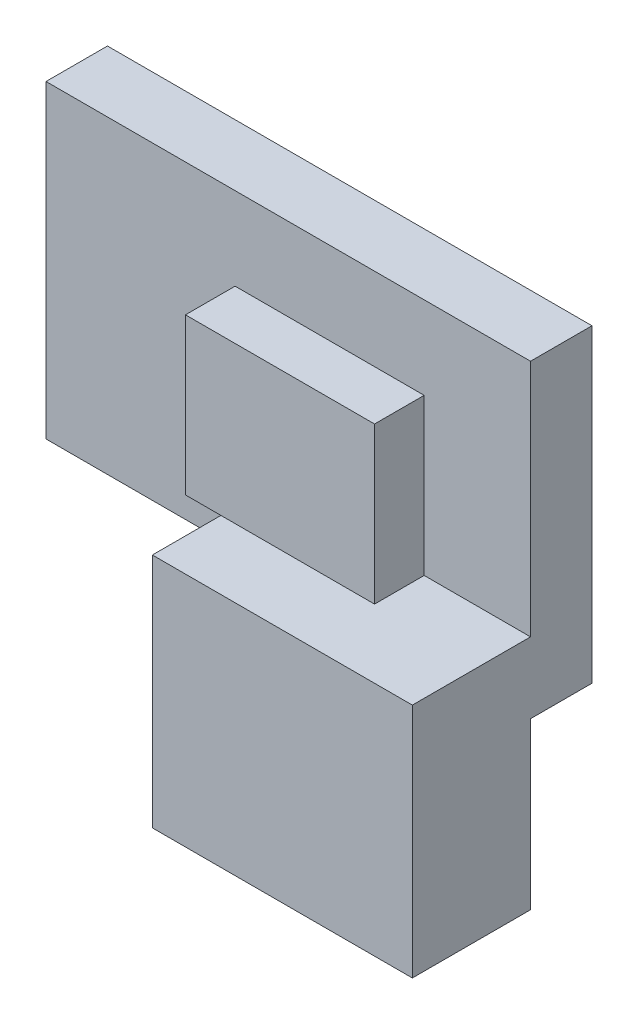
SolidWorks part; units mm, degrees
ref_plane "Plano frontal" through (0, 0, 0) normal (0, 0, 1) x (1, 0, 0)
ref_plane "Plano superior" through (0, 0, 0) normal (0, 1, 0) x (1, 0, 0)
ref_plane "Plano direito" through (0, 0, 0) normal (1, 0, 0) x (0, 0, -1)
sketch "PlacaEsboco" plane through (0, 0, 0) normal (0, 0, 1) x (1, 0, 0)
  line L1 (-10.25, -6.55) -> (10.25, -6.55)
  line L2 (-10.25, -6.55) -> (-10.25, 6.55)
  line L3 (-10.25, 6.55) -> (10.25, 6.55)
  line L4 (10.25, -6.55) -> (10.25, 6.55)
  line L5 (-10.25, -6.55) -> (10.25, 6.55) construction
  line L6 (-10.25, 6.55) -> (10.25, -6.55) construction
  point P0 (0, 0)
  dimension "D1" = 13.1
  dimension "D2" = 20.5
extrude "Placa" add sketch "PlacaEsboco" along normal mid plane 2.6
sketch "ConectorEsboco" plane through (0, 0, 1.3) normal (0, 0, 1) x (1, 0, 0)
  line L0 (10.25, -6.55) -> (10.25, 6.55) construction
  line L1 (10.25, -3.55) -> (-0.75, -3.55)
  line L2 (10.25, -3.55) -> (10.25, -13.55)
  line L3 (10.25, -13.55) -> (-0.75, -13.55)
  line L4 (-0.75, -3.55) -> (-0.75, -13.55)
  dimension "D1" = 11
  dimension "D2" = 10
  dimension "D3" = 3
extrude "Conector" add sketch "ConectorEsboco" along normal blind 5
sketch "ResistoresEsboco" plane through (0, 0, 1.3) normal (0, 0, 1) x (1, 0, 0)
  line L0 (10.25, -3.55) -> (-0.75, -3.55) construction
  line L1 (5.75, 3.05) -> (-2.25, 3.05)
  line L2 (5.75, 3.05) -> (5.75, -3.55)
  line L3 (5.75, -3.55) -> (-2.25, -3.55)
  line L4 (-2.25, 3.05) -> (-2.25, -3.55)
  dimension "D1" = 12.5
  dimension "D2" = 4.5
  dimension "D3" = 3.5
extrude "Resistores" add sketch "ResistoresEsboco" along normal blind 2.1
sketch "PosLedLDR" plane through (0, 0, 1.3) normal (0, 0, 1) x (1, 0, 0)
  line L0 (10.25, 6.55) -> (-10.25, 6.55) construction
  line L1 (-10.25, 6.55) -> (-10.25, -6.55) construction
  circle A0 centre (-6.25, 4.55) radius 0.25
  circle A1 centre (-6.25, 3.05) radius 0.25
  circle A2 centre (-6.25, -3.45) radius 0.25
  circle A3 centre (-6.25, -4.95) radius 0.25
  point P0 (-6.25, 4.55)
  point P1 (-6.25, 3.05)
  point P2 (-6.25, -3.45)
  point P3 (-6.25, -4.95)
  dimension "D6" = 0.5
  dimension "D7" = 0.5
  dimension "D8" = 0.5
  dimension "D9" = 0.5
  dimension "D1" = 2
  dimension "D2" = 4
  dimension "D3" = 1.5
  dimension "D4" = 1.5
  dimension "D5" = 6.5
